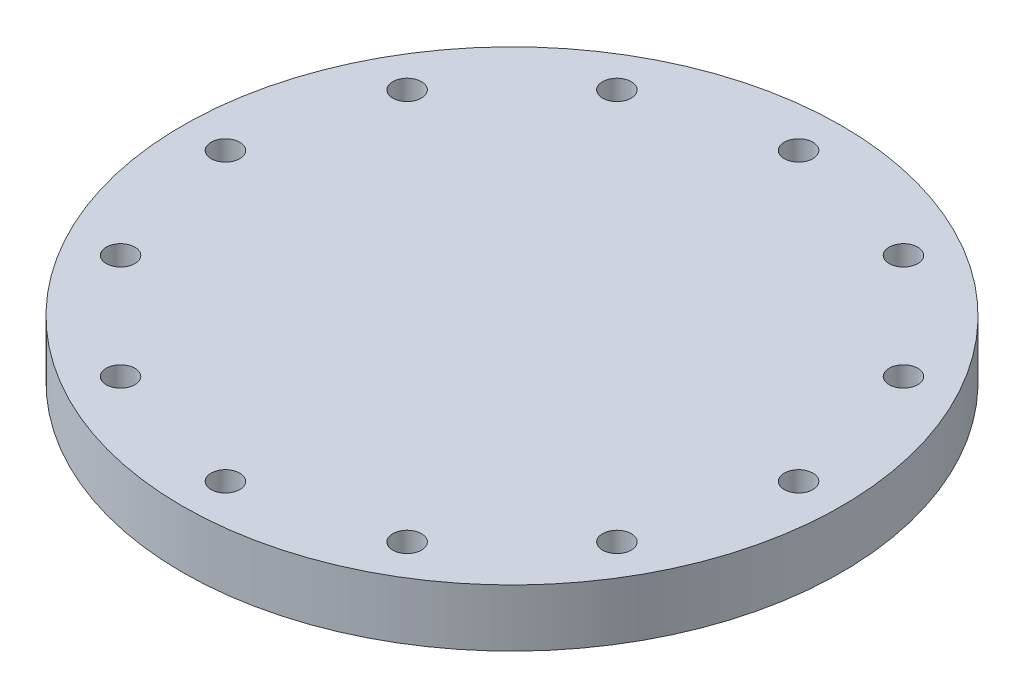
SolidWorks part; units mm, degrees
ref_plane "Front Plane" through (0, 0, 0) normal (0, 0, 1) x (1, 0, 0)
ref_plane "Top Plane" through (0, 0, 0) normal (0, 1, 0) x (1, 0, 0)
ref_plane "Right Plane" through (0, 0, 0) normal (1, 0, 0) x (0, 0, -1)
sketch "Sketch1" plane through (0, 0, 0) normal (0, 1, 0) x (1, 0, 0)
  circle A0 centre (0, 0) radius 115
  dimension "D1" = 230
extrude "Boss-Extrude1" add sketch "Sketch1" along normal blind 20
sketch "Sketch2" plane through (0, 20, 0) normal (0, 1, 0) x (1, 0, 0)
  circle A0 centre (0, 100) radius 5
  circle A1 centre (50, 86.6025) radius 5
  circle A2 centre (86.6025, 50) radius 5
  circle A3 centre (100, 0) radius 5
  circle A4 centre (86.6025, -50) radius 5
  circle A5 centre (50, -86.6025) radius 5
  circle A6 centre (0, -100) radius 5
  circle A7 centre (-50, -86.6025) radius 5
  circle A8 centre (-86.6025, -50) radius 5
  circle A9 centre (-100, 0) radius 5
  circle A10 centre (-86.6025, 50) radius 5
  circle A11 centre (-50, 86.6025) radius 5
  point P27 (0, 0)
  dimension "D2" = 10
  dimension "D1" = 100
  dimension "D3" = 12
extrude "Cut-Extrude1" cut sketch "Sketch2" against normal up to next
equation "\"D1@Sketch1\"=\"d\"+5*\"thiq\""
equation "\"d\" = 13"
equation "\"thiq\"= 2cm"
equation "\"D1@Sketch2\"= (\"d\"+(3.5*\"thiq\"))/2"
equation "\"screw\"= 1"
equation "\"D2@Sketch2\"= \"screw\""
